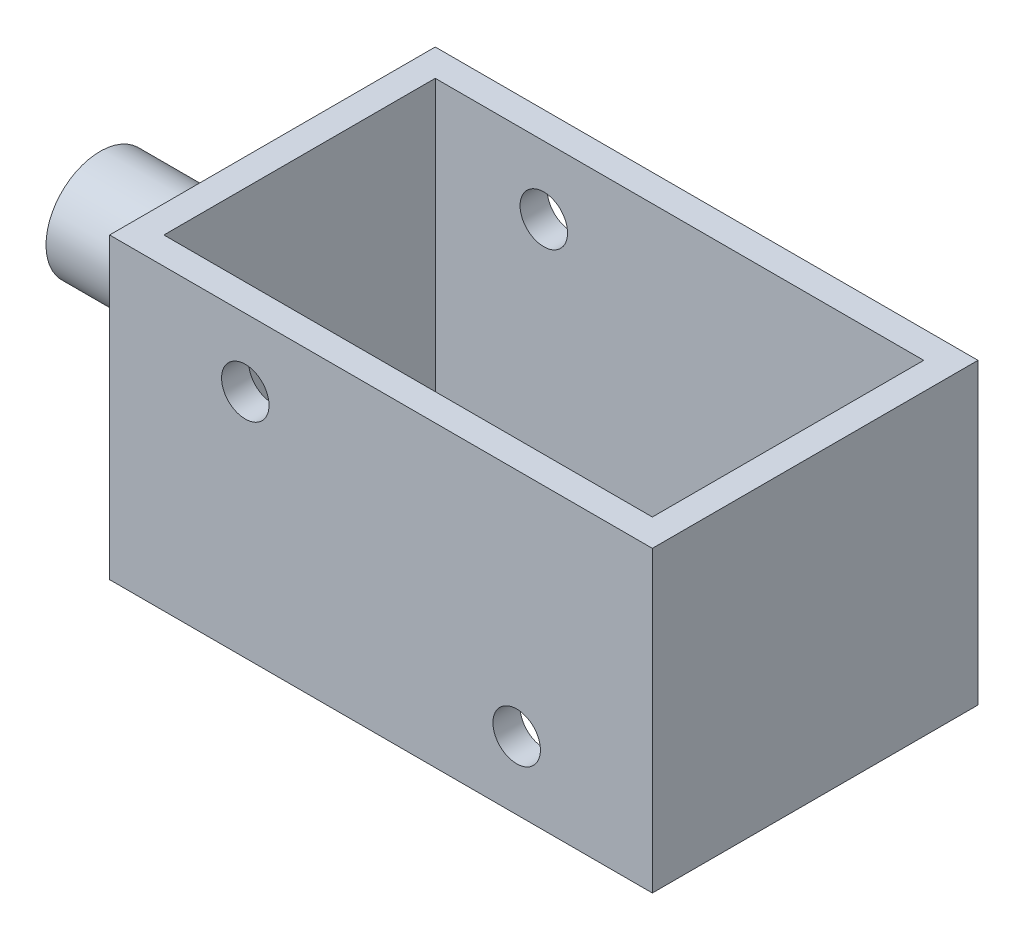
SolidWorks part; units mm, degrees
ref_plane "Front Plane" through (0, 0, 0) normal (0, 0, 1) x (1, 0, 0)
ref_plane "Top Plane" through (0, 0, 0) normal (0, 1, 0) x (1, 0, 0)
ref_plane "Right Plane" through (0, 0, 0) normal (1, 0, 0) x (0, 0, -1)
sketch "Sketch1" plane through (0, 0, 0) normal (0, 0, 1) x (1, 0, 0)
  line L0 (0, -5.5) -> (0, 5.5)
  line L1 (0, 5.5) -> (20, 5.5)
  line L2 (20, 5.5) -> (20, -5.5)
  line L3 (20, -5.5) -> (0, -5.5)
  dimension "D1" = 20
  dimension "D2" = 11
extrude "Boss-Extrude1" add sketch "Sketch1" along normal mid plane 12
shell "Shell1" thickness 1
sketch "Sketch2" plane through (0, 0, 0) normal (-1, 0, 0) x (0, 0, 1)
  circle A0 centre (0, 0) radius 1.9939
  dimension "D1" = 3.9878
extrude "Boss-Extrude2" add sketch "Sketch2" along normal blind 6.35
sketch "Sketch3" plane through (0, 0, 6) normal (0, 0, 1) x (1, 0, 0)
  line L0 (20, -5.5) -> (20, 5.5) construction
  line L1 (0, 5.5) -> (0, -5.5) construction
  circle A0 centre (5, 3) radius 0.875
  circle A1 centre (15, -3) radius 0.875
  point P4 (16.7336, -2.8313)
  point P5 (5.1622, 2.7233)
  point P10 (0, 0)
  dimension "D1" = 1.75
  dimension "D2" = 1.75
  dimension "D4" = 10
  dimension "D5" = 6
  dimension "D6" = 3
  dimension "D3" = 5
extrude "Cut-Extrude1" cut sketch "Sketch3" against normal through all
